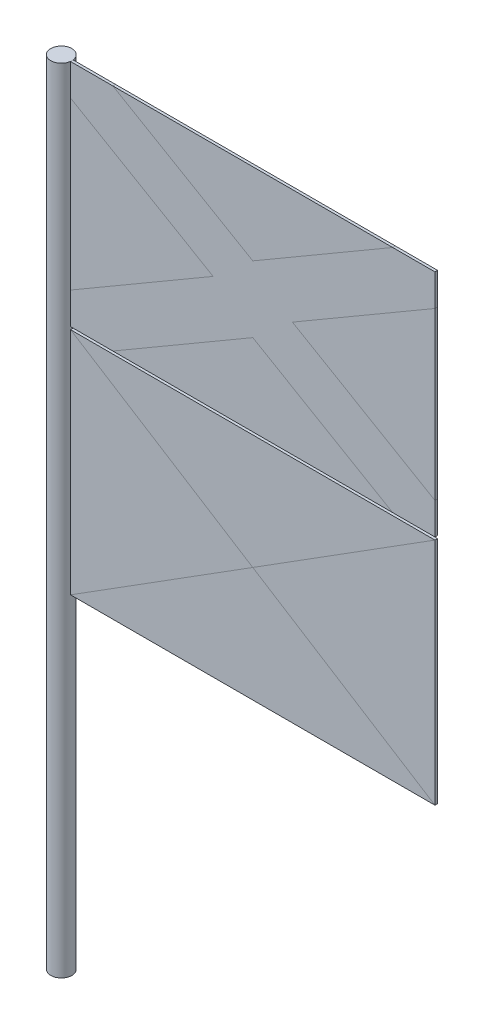
SolidWorks part; units mm, degrees
material "3.3535 (EN-AW 5754)"
ref_plane "Front" through (0, 0, 0) normal (0, 0, 1) x (1, 0, 0)
ref_plane "Top" through (0, 0, 0) normal (0, 1, 0) x (1, 0, 0)
ref_plane "Right" through (0, 0, 0) normal (1, 0, 0) x (0, 0, -1)
sketch "Esquisse2" plane through (0, 0, 0) normal (0, 0, 1) x (1, 0, 0)
  line L1 (2, 0) -> (71, 0)
  line L2 (2, 0) -> (2, -43.4783)
  line L3 (2, -43.4783) -> (71, -43.4783)
  line L4 (71, 0) -> (71, -43.4783)
  line L5 (2, -43.9783) -> (71, -43.9783)
  line L6 (2, -43.9783) -> (2, -87.4565)
  line L7 (2, -87.4565) -> (71, -87.4565)
  line L8 (71, -43.9783) -> (71, -87.4565)
  dimension "D1" = 0.5
  dimension "D4" = 87.4565
  dimension "D5" = 2
  dimension "D3" = 43.4783
  dimension "D6" = 90
  dimension "D2" = 69
extrude "Boss.-Extru.2" add sketch "Esquisse2" along normal mid plane 0.5 separate body
sketch "Esquisse3" plane through (0, 0, 0) normal (0, 1, 0) x (1, 0, 0)
  circle A0 centre (0, 0) radius 2
  dimension "D1" = 4
extrude "Boss.-Extru.3" add sketch "Esquisse3" against normal blind 150 separate body
sketch "Esquisse4" plane through (0, 0, 0.25) normal (0, 0, 1) x (1, 0, 0)
  line L0 (10, 0) -> (36.5, -15.4477)
  line L1 (71, 0) -> (2, 0) construction
  line L2 (36.5, -15.4477) -> (63, 0)
  line L3 (63, 0) -> (71, 0)
  line L4 (71, 0) -> (71, -6)
  line L5 (71, -43.4783) -> (71, 0) construction
  line L6 (71, -6) -> (44, -21.7391)
  line L7 (44, -21.7391) -> (71, -37.4783)
  line L8 (71, -37.4783) -> (71, -43.4783)
  line L9 (71, -43.4783) -> (63, -43.4783)
  line L10 (2, -43.4783) -> (71, -43.4783) construction
  line L11 (63, -43.4783) -> (36.5, -28.0306)
  line L12 (36.5, -28.0306) -> (10, -43.4783)
  line L13 (10, -43.4783) -> (2, -43.4783)
  line L14 (2, -43.4783) -> (2, -37.4783)
  line L15 (2, 0) -> (2, -43.4783) construction
  line L16 (2, -37.4783) -> (29, -21.7391)
  line L17 (29, -21.7391) -> (2, -6)
  line L18 (2, -6) -> (2, 0)
  line L19 (2, 0) -> (10, 0)
  dimension "D1" = 8
  dimension "D2" = 6
  dimension "D3" = 27
split "Fractionner1" trim tools "Esquisse4" bodies to split 103 resulting bodies 129 130 131 132 133
sketch "Esquisse6" plane through (0, 0, 0.25) normal (0, 0, 1) x (1, 0, 0)
  line L0 (2, -43.9783) -> (71, -43.9783)
  line L1 (71, -43.9783) -> (36.5, -65.7174)
  line L2 (36.5, -65.7174) -> (2, -43.9783)
  line L3 (2, -87.4565) -> (36.5, -65.7174) construction
  line L4 (71, -87.4565) -> (36.5, -65.7174) construction
split "Fractionner2" trim tools "Esquisse6" bodies to split 102 resulting bodies 134 135
sketch "Esquisse7" plane through (0, 0, 0.25) normal (0, 0, 1) x (1, 0, 0)
  line L0 (2, -87.4565) -> (36.5, -65.7174)
  line L1 (36.5, -65.7174) -> (71, -87.4565)
  line L2 (71, -87.4565) -> (2, -87.4565)
split "Fractionner3" trim tools "Esquisse7" bodies to split 134 resulting bodies 136 137 138
equation "\"D3@Esquisse2\"=3000/\"D2@Esquisse2\""
